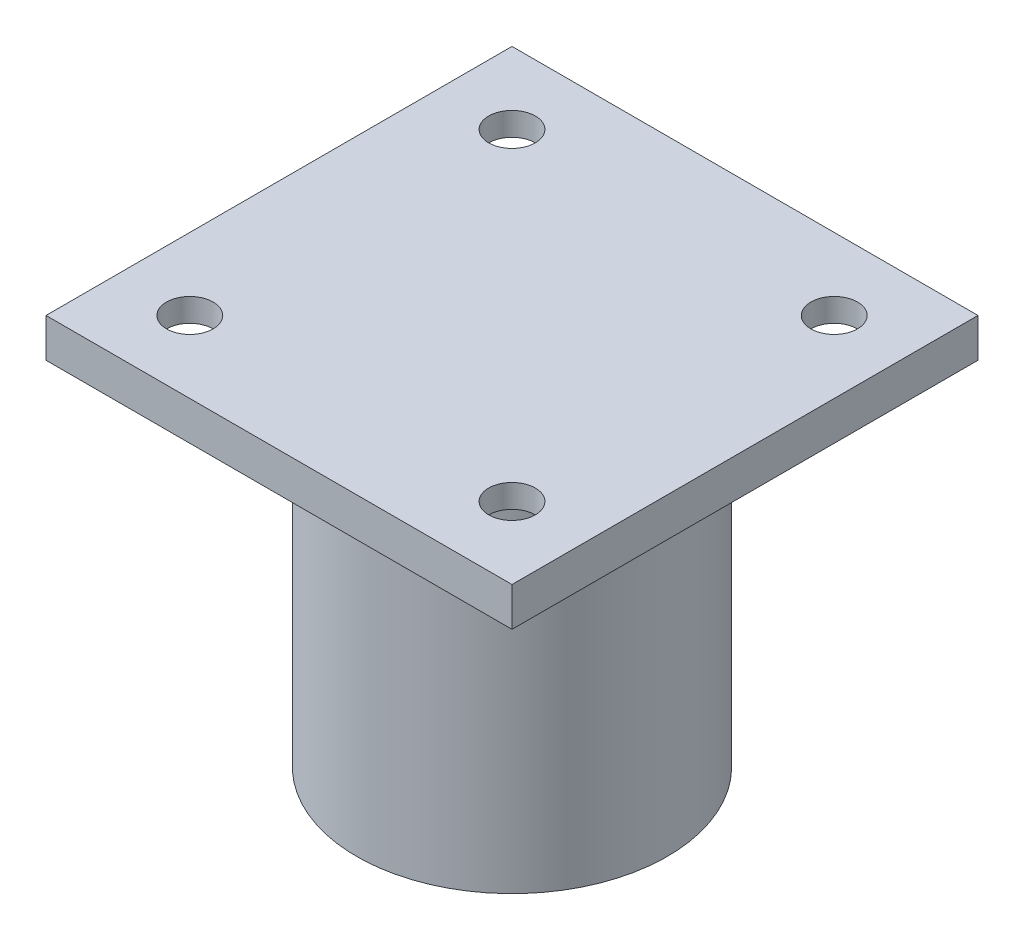
SolidWorks part; units mm, degrees
ref_plane "Front Plane" through (0, 0, 0) normal (0, 0, 1) x (1, 0, 0)
ref_plane "Top Plane" through (0, 0, 0) normal (0, 1, 0) x (1, 0, 0)
ref_plane "Right Plane" through (0, 0, 0) normal (1, 0, 0) x (0, 0, -1)
sketch "Sketch1" plane through (0, 0, 0) normal (0, 1, 0) x (1, 0, 0)
  line L1 (-22.5, 22.5) -> (22.5, 22.5)
  line L2 (-22.5, 22.5) -> (-22.5, -22.5)
  line L3 (-22.5, -22.5) -> (22.5, -22.5)
  line L4 (22.5, 22.5) -> (22.5, -22.5)
  line L5 (-22.5, 22.5) -> (22.5, -22.5) construction
  line L6 (-22.5, -22.5) -> (22.5, 22.5) construction
  point P0 (0, 0)
  dimension "D1" = 45
extrude "Boss-Extrude1" add sketch "Sketch1" along normal blind 3.75
sketch "Sketch2" plane through (0, 0, 0) normal (0, -1, 0) x (1, 0, 0)
  circle A0 centre (0, 0) radius 15
  dimension "D1" = 30
extrude "Boss-Extrude2" add sketch "Sketch2" along normal blind 34
sketch "Sketch3" plane through (0, 3.75, 0) normal (0, 1, 0) x (1, 0, 0)
  line L0 (0, 22.5) -> (0, -22.5) construction
  line L1 (22.5, 22.5) -> (-22.5, 22.5) construction
  line L2 (-22.5, -22.5) -> (22.5, -22.5) construction
  line L3 (0, 0) -> (15.5563, 15.5563) construction
  line L4 (0, 0) -> (-15.5563, -15.5563) construction
  circle A0 centre (15.5563, 15.5563) radius 2.25
  circle A1 centre (15.5563, -15.5563) radius 2.25
  circle A2 centre (-15.5563, -15.5563) radius 2.25
  circle A3 centre (-15.5563, 15.5563) radius 2.25
  dimension "D2" = 4.5
  dimension "D1" = 45
  dimension "D3" = 22
  dimension "D4" = 4
extrude "Cut-Extrude1" cut sketch "Sketch3" against normal through all
sketch "Sketch4" plane through (0, 0, 0) normal (0, -1, 0) x (1, 0, 0)
  line L0 (0, 22.5) -> (0, -22.5) construction
  line L1 (-22.5, 22.5) -> (22.5, 22.5) construction
  line L2 (22.5, -22.5) -> (-22.5, -22.5) construction
  line L3 (-22.5, 0) -> (22.5, 0) construction
  line L4 (-22.5, -22.5) -> (-22.5, 22.5) construction
  line L5 (22.5, 22.5) -> (22.5, -22.5) construction
  circle A0 centre (-15.5563, 15.5563) radius 5
  circle A1 centre (15.5563, 15.5563) radius 5
  circle A2 centre (15.5563, -15.5563) radius 5
  circle A3 centre (-15.5563, -15.5563) radius 5
  dimension "D1" = 10
extrude "Cut-Extrude2" cut sketch "Sketch4" against normal blind 1.5
sketch "Sketch5" plane through (0, -34, 0) normal (0, -1, 0) x (1, 0, 0)
  line L0 (-7.5, 0) -> (0, 0) construction
  line L1 (0, 0) -> (7.5, 0) construction
  circle A0 centre (7.5, 0) radius 1.55
  circle A1 centre (0, -7.5) radius 1.55
  circle A2 centre (-7.5, 0) radius 1.55
  circle A3 centre (0, 7.5) radius 1.55
  point P2 (0, 0)
  point P5 (-9.0213, 0)
  point P12 (0, 0)
  point P13 (0, 0)
  dimension "D2" = 3.1
  dimension "D1" = 7.5
  dimension "D3" = 4
extrude "Cut-Extrude3" cut sketch "Sketch5" against normal blind 15
sketch "Sketch7" plane through (0, 0, 0) normal (0, -1, 0) x (1, 0, 0)
  circle A0 centre (0, 0) radius 17
  circle A1 centre (15.5563, -15.5563) radius 5 construction
extrude "Boss-Extrude3" add sketch "Sketch7" along normal blind 4
